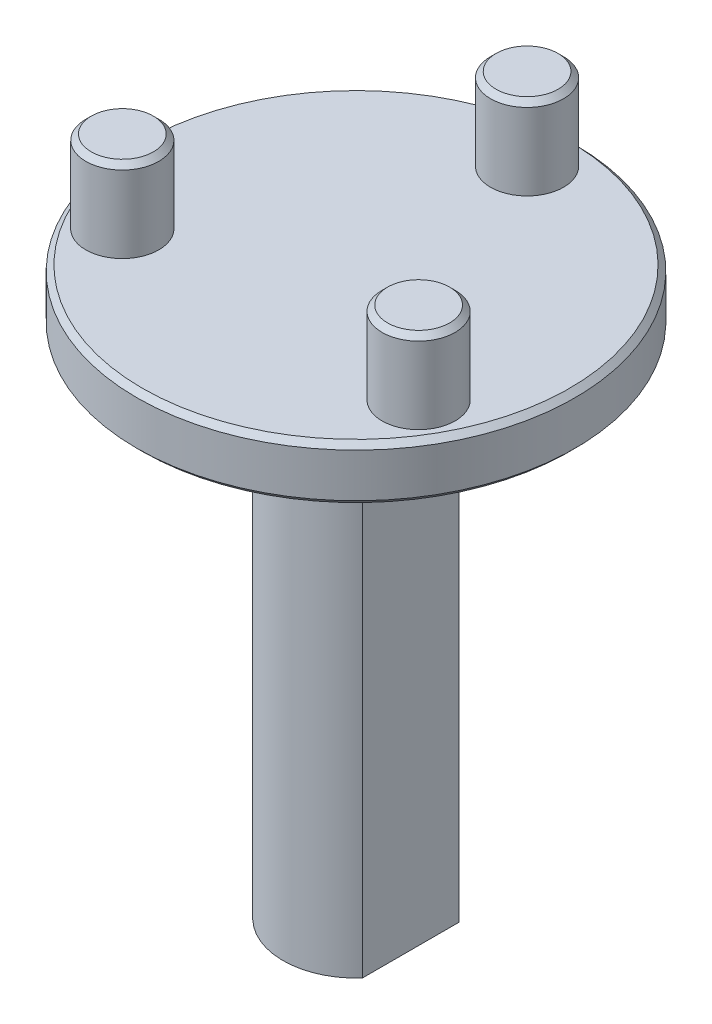
SolidWorks part; units mm, degrees
ref_plane "Front Plane" through (0, 0, 0) normal (0, 0, 1) x (1, 0, 0)
ref_plane "Top Plane" through (0, 0, 0) normal (0, 1, 0) x (1, 0, 0)
ref_plane "Right Plane" through (0, 0, 0) normal (1, 0, 0) x (0, 0, -1)
sketch "Sketch1" plane through (0, 0, 0) normal (0, 1, 0) x (1, 0, 0)
  circle A0 centre (0, 0) radius 12
  dimension "D1" = 24
extrude "Boss-Extrude1" add sketch "Sketch1" along normal blind 3
sketch "Sketch2" plane through (0, 3, 0) normal (0, 1, 0) x (1, 0, 0)
  line L0 (0, 9.37) -> (0, 0) construction
  line L1 (0, 0) -> (-8.1147, -4.685) construction
  line L2 (0, 0) -> (8.1147, -4.685) construction
  circle A0 centre (0, 9.37) radius 2
  circle A1 centre (-8.1147, -4.685) radius 2
  circle A2 centre (8.1147, -4.685) radius 2
  dimension "D4" = 4
  dimension "D5" = 4
  dimension "D6" = 4
  dimension "D1" = 120
  dimension "D2" = 120
  dimension "D3" = 9.37
extrude "Boss-Extrude2" add sketch "Sketch2" along normal blind 4.5
sketch "Sketch3" plane through (0, 0, 0) normal (0, -1, 0) x (1, 0, 0)
  circle A0 centre (0, 0) radius 5
  dimension "D1" = 10
extrude "Boss-Extrude3" add sketch "Sketch3" along normal blind 1
sketch "Sketch4" plane through (0, -1, 0) normal (0, -1, 0) x (1, 0, 0)
  line L0 (-4, 0) -> (3, 0) construction
  line L1 (3, 2.6458) -> (3, -2.6458)
  arc A0 (3, 2.6458) -> (3, -2.6458) centre (0, 0) ccw
  dimension "D1" = 8
  dimension "D2" = 7
extrude "Boss-Extrude4" add sketch "Sketch4" along normal blind 27
chamfer "Chamfer1" distance 0.3 angle 45 5 edges at (-8.1147, 7.5, 6.685) (0, 0, 12) (0, 3, 12) (0, 7.5, -7.37) (8.1147, 7.5, 6.685)
